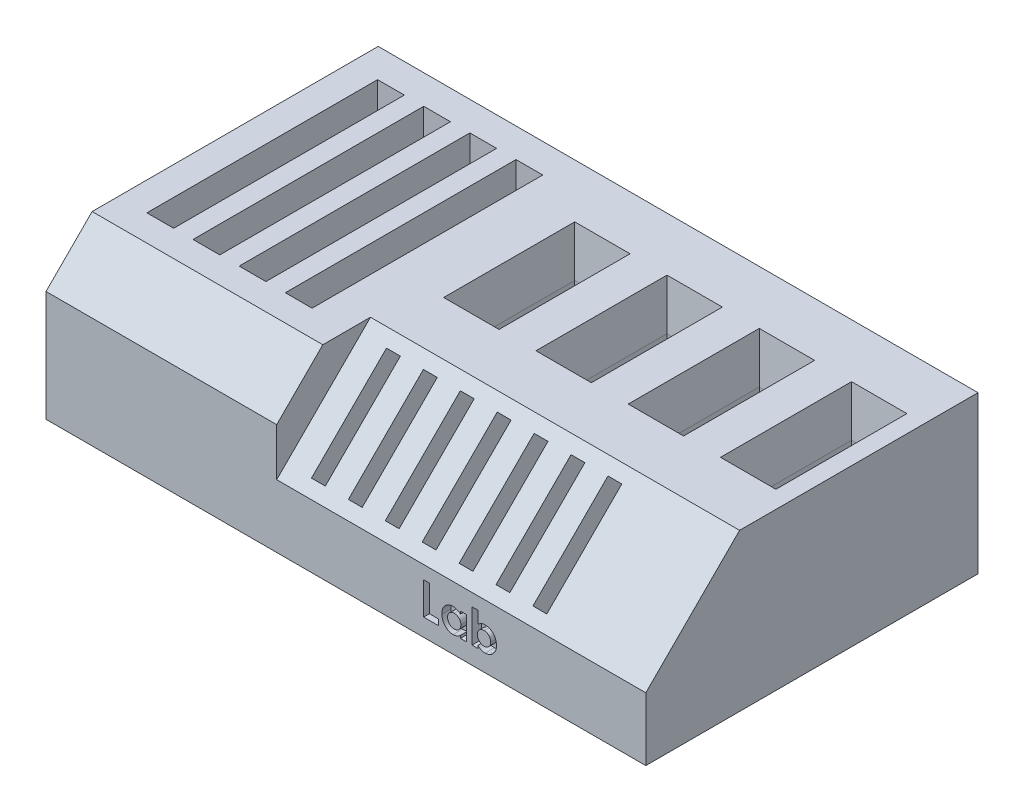
SolidWorks part; units mm, degrees
ref_plane "Alzado" through (0, 0, 0) normal (0, 0, 1) x (1, 0, 0)
ref_plane "Planta" through (0, 0, 0) normal (0, 1, 0) x (1, 0, 0)
ref_plane "Vista lateral" through (0, 0, 0) normal (1, 0, 0) x (0, 0, -1)
sketch "Croquis1" plane through (0, 0, 0) normal (1, 0, 0) x (0, 0, -1)
  line L1 (18, -8.5) -> (-18, -8.5)
  line L2 (18, -8.5) -> (18, 8.5)
  line L3 (18, 8.5) -> (-18, 8.5)
  line L4 (-18, -8.5) -> (-18, 8.5)
  line L5 (18, -8.5) -> (-18, 8.5) construction
  line L6 (18, 8.5) -> (-18, -8.5) construction
  point P0 (0, 0)
  dimension "D1" = 17
  dimension "D2" = 36
extrude "Saliente-Extruir1" add sketch "Croquis1" along normal blind 65
chamfer "Chaflán1" distance 5 angle 45 1 edges at (32.5, 8.5, 18)
sketch "Croquis2" plane through (0, 8.5, 0) normal (0, 1, 0) x (1, 0, 0)
  line L0 (8.0873, 14.8463) -> (8.0873, -10.1537)
  line L1 (3.0873, 14.8463) -> (5.9873, 14.8463)
  line L2 (3.0873, 14.8463) -> (3.0873, -10.1537)
  line L3 (3.0873, -10.1537) -> (5.9873, -10.1537)
  line L4 (5.9873, 14.8463) -> (5.9873, -10.1537)
  line L5 (10.9873, 14.8463) -> (10.9873, -10.1537)
  line L6 (8.0873, 14.8463) -> (10.9873, 14.8463)
  line L7 (8.0873, -10.1537) -> (10.9873, -10.1537)
  line L8 (13.0873, 14.8463) -> (13.0873, -10.1537)
  line L9 (15.9873, 14.8463) -> (15.9873, -10.1537)
  line L10 (13.0873, 14.8463) -> (15.9873, 14.8463)
  line L11 (13.0873, -10.1537) -> (15.9873, -10.1537)
  line L12 (18.0873, 14.8463) -> (18.0873, -10.1537)
  line L13 (20.9873, 14.8463) -> (20.9873, -10.1537)
  line L14 (18.0873, 14.8463) -> (20.9873, 14.8463)
  line L15 (18.0873, -10.1537) -> (20.9873, -10.1537)
  dimension "D1" = 25
  dimension "D2" = 2.9
  dimension "D3" = 4
sketch "Croquis4" plane through (0, 8.5, 0) normal (0, 1, 0) x (1, 0, 0)
  line L0 (0, 2.5) -> (79.8883, 2.5) construction
  line L1 (0, 18) -> (0, -13) construction
extrude "Cortar-Extruir1" cut sketch "Croquis2" against normal blind 14
sketch "Croquis6" plane through (0, 0, 18) normal (0, 0, 1) x (1, 0, 0)
  line L1 (65, -8.5) -> (25, -8.5)
  line L2 (65, -8.5) -> (65, -1.6649)
  line L3 (65, -1.6649) -> (25, -1.6649)
  line L4 (25, -8.5) -> (25, -1.6649)
sketch "Croquis7" plane through (65, 0, 0) normal (1, 0, 0) x (0, 0, -1)
  line L0 (-18, -1.6649) -> (-7.8351, 8.5)
  line L1 (18, 8.5) -> (-13, 8.5) construction
  line L2 (-18, -1.6649) -> (-18, 3.5)
  line L3 (-18, 3.5) -> (-13, 8.5)
  line L4 (-13, 8.5) -> (-7.8351, 8.5)
extrude "Cortar-Extruir2" cut sketch "Croquis7" against normal blind 40
sketch "Croquis9" plane through (0, 8.1676, 8.1676) normal (0, 0.7071, 0.7071) x (1, 0, 0)
  line L0 (65, -6.7175) -> (20.5299, -6.7175) construction
  line L1 (27.7521, -0.9675) -> (29.2521, -0.9675)
  line L2 (27.7521, -0.9675) -> (27.7521, -12.4675)
  line L3 (27.7521, -12.4675) -> (29.2521, -12.4675)
  line L4 (29.2521, -0.9675) -> (29.2521, -12.4675)
  line L5 (65, -13.9052) -> (65, 0.4702) construction
  line L6 (31.7521, -0.9675) -> (31.7521, -12.4675)
  line L7 (31.7521, -0.9675) -> (33.2521, -0.9675)
  line L8 (33.2521, -0.9675) -> (33.2521, -12.4675)
  line L9 (31.7521, -12.4675) -> (33.2521, -12.4675)
  line L10 (35.7521, -0.9675) -> (35.7521, -12.4675)
  line L11 (35.7521, -0.9675) -> (37.2521, -0.9675)
  line L12 (37.2521, -0.9675) -> (37.2521, -12.4675)
  line L13 (35.7521, -12.4675) -> (37.2521, -12.4675)
  line L14 (39.7521, -0.9675) -> (39.7521, -12.4675)
  line L15 (39.7521, -0.9675) -> (41.2521, -0.9675)
  line L16 (41.2521, -0.9675) -> (41.2521, -12.4675)
  line L17 (39.7521, -12.4675) -> (41.2521, -12.4675)
  line L18 (43.7521, -0.9675) -> (43.7521, -12.4675)
  line L19 (43.7521, -0.9675) -> (45.2521, -0.9675)
  line L20 (45.2521, -0.9675) -> (45.2521, -12.4675)
  line L21 (43.7521, -12.4675) -> (45.2521, -12.4675)
  line L22 (47.7521, -0.9675) -> (47.7521, -12.4675)
  line L23 (47.7521, -0.9675) -> (49.2521, -0.9675)
  line L24 (49.2521, -0.9675) -> (49.2521, -12.4675)
  line L25 (47.7521, -12.4675) -> (49.2521, -12.4675)
  line L26 (51.7521, -0.9675) -> (51.7521, -12.4675)
  line L27 (51.7521, -0.9675) -> (53.2521, -0.9675)
  line L28 (53.2521, -0.9675) -> (53.2521, -12.4675)
  line L29 (51.7521, -12.4675) -> (53.2521, -12.4675)
  dimension "D1" = 7
extrude "Cortar-Extruir3" cut sketch "Croquis9" against normal blind 10
sketch "Croquis10" plane through (0, 8.5, 0) normal (0, 1, 0) x (1, 0, 0)
  line L0 (65, 5.0824) -> (22.8646, 5.0824) construction
  line L1 (65, 18) -> (65, -7.8351) construction
  line L2 (42.6142, 11.6824) -> (37.6142, 11.6824)
  line L3 (32.6142, -1.5176) -> (27.6142, -1.5176)
  line L4 (32.6142, -1.5176) -> (32.6142, 11.6824)
  line L5 (32.6142, 11.6824) -> (27.6142, 11.6824)
  line L6 (27.6142, -1.5176) -> (27.6142, 11.6824)
  line L7 (32.6142, -1.5176) -> (27.6142, 11.6824) construction
  line L8 (32.6142, 11.6824) -> (27.6142, -1.5176) construction
  line L9 (42.6142, -1.5176) -> (37.6142, -1.5176)
  line L10 (75, 5.0824) -> (32.8646, 5.0824) construction
  line L11 (37.6142, -1.5176) -> (37.6142, 11.6824)
  line L12 (42.6142, -1.5176) -> (42.6142, 11.6824)
  line L13 (52.6142, 11.6824) -> (47.6142, 11.6824)
  line L14 (52.6142, -1.5176) -> (47.6142, -1.5176)
  line L15 (85, 5.0824) -> (42.8646, 5.0824) construction
  line L16 (47.6142, -1.5176) -> (47.6142, 11.6824)
  line L17 (52.6142, -1.5176) -> (52.6142, 11.6824)
  line L18 (62.6142, 11.6824) -> (57.6142, 11.6824)
  line L19 (62.6142, -1.5176) -> (57.6142, -1.5176)
  line L20 (95, 5.0824) -> (52.8646, 5.0824) construction
  line L21 (57.6142, -1.5176) -> (57.6142, 11.6824)
  line L22 (62.6142, -1.5176) -> (62.6142, 11.6824)
  point P4 (30.1142, 5.0824)
  dimension "D1" = 4
extrude "Cortar-Extruir4" cut sketch "Croquis10" against normal blind 13
sketch "Croquis11" plane through (0, 0, 18) normal (0, 0, 1) x (1, 0, 0)
  text T0 "<b>Lab</b>"
chamfer "Chaflán2" distance 0.5 distance2 5 1 edges at (27.6142, 8.5, -5.0824)
chamfer "Chaflán4" distance 0.5 distance2 5 3 edges at (29.8642, 8.5, 1.5176) (32.6142, 8.5, -5.0824) (29.8642, 8.5, -11.6824)
chamfer "Chaflán5" distance 0.5 distance2 5 12 edges at (60.1142, 8.5, 1.5176) (62.6142, 8.5, -5.0824) (60.1142, 8.5, -11.6824) (57.6142, 8.5, -5.0824) (50.1142, 8.5, 1.5176) (52.6142, 8.5, -5.0824) (50.1142, 8.5, -11.6824) (47.6142, 8.5, -5.0824) (40.1142, 8.5, 1.5176) (42.6142, 8.5, -5.0824) (40.1142, 8.5, -11.6824) (37.6142, 8.5, -5.0824)
extrude "Cortar-Extruir5" cut sketch "Croquis11" against normal blind 1
sketch "Croquis5" plane through (0, 0, 0) normal (-1, 0, 0) x (0, 0, 1)
